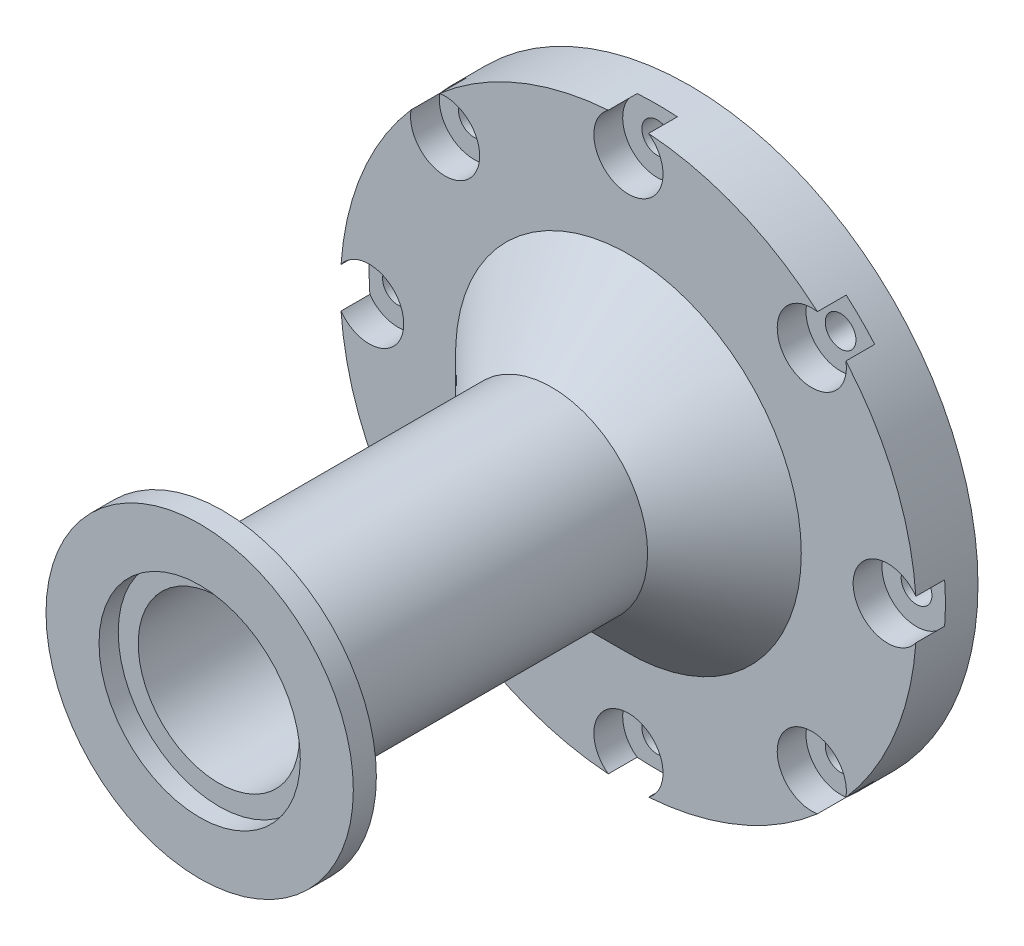
SolidWorks part; units mm, degrees
material "AISI 304"
ref_plane "Front Plane" through (0, 0, 0) normal (0, 0, 1) x (1, 0, 0)
ref_plane "Top Plane" through (0, 0, 0) normal (0, 1, 0) x (1, 0, 0)
ref_plane "Right Plane" through (0, 0, 0) normal (1, 0, 0) x (0, 0, -1)
sketch "Sketch1" plane through (0, 0, 0) normal (0, 0, 1) x (1, 0, 0)
  circle A0 centre (0, 0) radius 20.71 construction
  circle A1 centre (0, 0) radius 20.71
  circle A2 centre (0, 0) radius 19.21 construction
  circle A3 centre (0, 0) radius 19.21
  circle A5 centre (0, 0) radius 37.5 construction
  circle A6 centre (23.8649, -23.8649) radius 2 construction
  circle A7 centre (33.75, 0) radius 2 construction
  circle A8 centre (-23.8649, 23.8649) radius 2 construction
  circle A9 centre (-33.75, 0) radius 2 construction
  circle A10 centre (-23.8649, -23.8649) radius 2 construction
  circle A11 centre (0, -33.75) radius 2 construction
  circle A12 centre (23.8649, -23.8649) radius 2
  circle A13 centre (33.75, 0) radius 2
  circle A14 centre (-23.8649, 23.8649) radius 2
  circle A15 centre (-33.75, 0) radius 2
  circle A16 centre (-23.8649, -23.8649) radius 2
  circle A17 centre (0, -33.75) radius 2
  circle A18 centre (0, 0) radius 37.5
sketch "Sketch2" plane through (0, 0, 0) normal (0, 0, 1) x (1, 0, 0)
  circle A1 centre (0, 0) radius 37.5 construction
  circle A2 centre (0, 0) radius 5.35 construction
  circle A3 centre (0, 0) radius 5.35
  circle A4 centre (0, 0) radius 37.5
extrude "Boss-Extrude2" add sketch "Sketch2" along normal blind 8
sketch "Sketch3" plane through (0, 0, 0) normal (0, 0, 1) x (1, 0, 0)
  circle A0 centre (0, 0) radius 20.71 construction
  circle A1 centre (0, 0) radius 20.71
  circle A2 centre (0, 0) radius 19.21 construction
  circle A3 centre (0, 0) radius 19.21
sketch "Sketch14" plane through (0, 0, 0) normal (0, 0, 1) x (1, 0, 0)
  circle A7 centre (0, 33.75) radius 2
  circle A8 centre (0, 33.75) radius 2
  circle A9 centre (-23.8649, 23.8649) radius 2
  circle A10 centre (-23.8649, 23.8649) radius 2
  circle A11 centre (-33.75, 0) radius 2
  circle A12 centre (-33.75, 0) radius 2
  circle A13 centre (-23.8649, -23.8649) radius 2
  circle A14 centre (-23.8649, -23.8649) radius 2
  circle A15 centre (0, -33.75) radius 2
  circle A16 centre (0, -33.75) radius 2
  circle A17 centre (23.8649, -23.8649) radius 2
  circle A18 centre (23.8649, -23.8649) radius 2
  circle A19 centre (33.75, 0) radius 2
  circle A20 centre (33.75, 0) radius 2
  circle A21 centre (23.8649, 23.8649) radius 2
  circle A22 centre (23.8649, 23.8649) radius 2
  dimension "D1" = 0
  dimension "D2" = 0
  dimension "D3" = 0
  dimension "D4" = 0
  dimension "D5" = 0
  dimension "D6" = 0
  dimension "D7" = 0
  dimension "D8" = 0
extrude "Cut-Extrude6" cut sketch "Sketch14" along normal through all
extrude "Cut-Extrude2" cut sketch "Sketch3" along normal blind 2
sketch "Sketch6" plane through (0, 0, 8) normal (0, 0, 1) x (1, 0, 0)
  circle A1 centre (0, 0) radius 10.45
  circle A2 centre (0, 0) radius 5.35 construction
  circle A3 centre (0, 0) radius 6.45
  dimension "D1" = 1.1
  dimension "D2" = 4
extrude "Boss-Extrude3" [suppressed] add sketch "Sketch6" along normal blind 40
sketch "Sketch7" plane through (0, 0, 8) normal (0, 0, 1) x (1, 0, 0)
  circle A0 centre (0, 0) radius 12.5
  circle A1 centre (0, 0) radius 10.5
  dimension "D1" = 25
  dimension "D2" = 2
extrude "Boss-Extrude4" add sketch "Sketch7" along normal blind 50.8
sketch "Sketch10" plane through (0, 0, 58.8) normal (0, 0, 1) x (1, 0, 0)
  circle A0 centre (0, 0) radius 12.5 construction
  circle A1 centre (0, 0) radius 12.5
extrude "Boss-Extrude5" add sketch "Sketch10" along normal blind 2.01 draft 75 draft outward yes
sketch "Sketch11" plane through (0, 0, 60.81) normal (0, 0, 1) x (1, 0, 0)
  circle A1 centre (0, 0) radius 10.5 construction
  circle A2 centre (0, 0) radius 10.5
extrude "Cut-Extrude3" cut sketch "Sketch11" against normal through all
sketch "Sketch12" plane through (0, 0, 60.81) normal (0, 0, 1) x (1, 0, 0)
  circle A0 centre (0, 0) radius 10.5 construction
  circle A1 centre (0, 0) radius 20.0014 construction
  circle A2 centre (0, 0) radius 10.5
  circle A3 centre (0, 0) radius 20.0014
extrude "Boss-Extrude6" add sketch "Sketch12" along normal blind 3
sketch "Sketch13" plane through (0, 0, 63.81) normal (0, 0, 1) x (1, 0, 0)
  circle A0 centre (0, 0) radius 13.1
  dimension "D1" = 26.2
extrude "Cut-Extrude4" cut sketch "Sketch13" against normal blind 2.5
chamfer "Chamfer1" distance 10 angle 45 1 edges at (12.5, 0, 8)
chamfer "Chamfer2" [suppressed] distance 10 angle 45
sketch "Sketch15" [suppressed] plane through (0, 0, 48) normal (0, 0, 1) x (1, 0, 0)
  circle A2 centre (0, 0) radius 7.35
  circle A3 centre (0, 0) radius 7.35
  dimension "D1" = 2
extrude "Cut-Extrude7" [suppressed] cut sketch "Sketch15" against normal blind 10
sketch "Sketch17" plane through (0, 0, 8) normal (0, 0, 1) x (1, 0, 0)
  circle A1 centre (-23.8649, 23.8649) radius 4.5
  circle A2 centre (-33.75, 0) radius 4.5
  circle A3 centre (-33.75, 0) radius 4.5
  circle A4 centre (0, 33.75) radius 4.5
  circle A5 centre (23.8649, 23.8649) radius 4.5
  circle A6 centre (33.75, 0) radius 4.5
  circle A7 centre (23.8649, -23.8649) radius 4.5
  circle A8 centre (0, -33.75) radius 4.5
  circle A9 centre (-23.8649, -23.8649) radius 4.5
  point P19 (0, 0)
  dimension "D1" = 2.5
  dimension "D2" = 8
extrude "Cut-Extrude8" cut sketch "Sketch17" against normal blind 3.75
